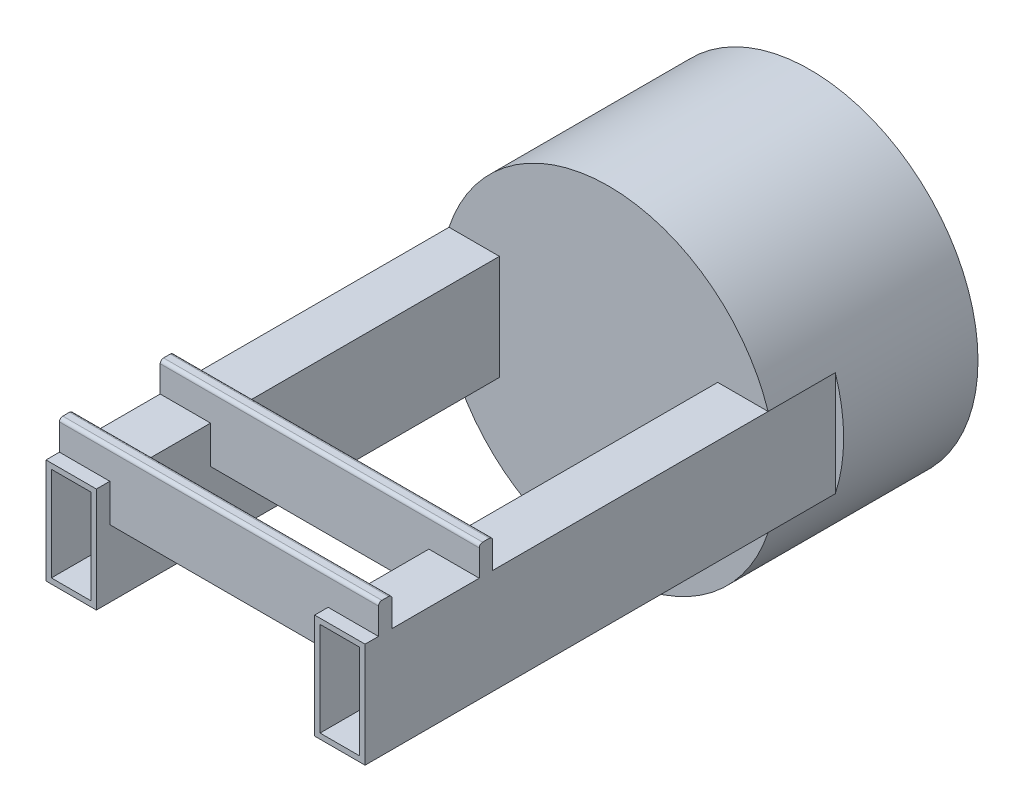
SolidWorks part; units mm, degrees
ref_plane "Ön Düzlem" through (0, 0, 0) normal (0, 0, 1) x (1, 0, 0)
ref_plane "Üst Düzlem" through (0, 0, 0) normal (0, 1, 0) x (1, 0, 0)
ref_plane "Sağ Düzlem" through (0, 0, 0) normal (1, 0, 0) x (0, 0, -1)
sketch "Çizim1" plane through (0, 0, 0) normal (0, 0, 1) x (1, 0, 0)
  line L0 (0, 265.92) -> (0, -189.5261) construction
  line L1 (-369.2295, 0) -> (436.5598, 0) construction
  line L2 (162.5, -78.0625) -> (162.5, 78.0625)
  line L3 (-162.5, -78.0625) -> (-237.5, -78.0625)
  line L4 (-162.5, -78.0625) -> (-162.5, 78.0625)
  line L5 (-162.5, 78.0625) -> (-237.5, 78.0625)
  line L6 (-237.5, -78.0625) -> (-237.5, 78.0625)
  line L7 (-162.5, -78.0625) -> (-237.5, 78.0625) construction
  line L8 (-162.5, 78.0625) -> (-237.5, -78.0625) construction
  line L9 (162.5, -78.0625) -> (237.5, -78.0625)
  line L10 (237.5, -78.0625) -> (237.5, 78.0625)
  line L11 (162.5, 78.0625) -> (237.5, 78.0625)
  arc A0 (-237.5, -78.0625) -> (237.5, -78.0625) centre (0, 0) ccw
  arc A1 (237.5, 78.0625) -> (-237.5, 78.0625) centre (0, 0) ccw
  point P7 (-200, 0)
  dimension "D1" = 500
  dimension "D2" = 200
  dimension "D3" = 75
extrude "Yükseklik-Ekstrüzyon2" add sketch "Çizim1" along normal blind 100 contours L11 A1 L5 L4 L3 A0 L9 L2 | L6 L3 L4 L5 | L11 L2 L9 L10
sketch "Çizim3" plane through (0, 0, 100) normal (0, 0, 1) x (1, 0, 0)
  line L0 (0, 0) -> (0, 358.8642) construction
  line L1 (0, 358.8642) -> (0, -328.59) construction
  line L2 (-380.3126, 0) -> (372.367, 0) construction
  line L3 (237.5, 78.0625) -> (237.5, -78.0625)
  line L4 (-237.5, 78.0625) -> (-162.5, 78.0625)
  line L5 (-237.5, 78.0625) -> (-237.5, -78.0625)
  line L6 (-237.5, -78.0625) -> (-162.5, -78.0625)
  line L7 (-162.5, 78.0625) -> (-162.5, -78.0625)
  line L8 (-237.5, 78.0625) -> (-162.5, -78.0625) construction
  line L9 (-237.5, -78.0625) -> (-162.5, 78.0625) construction
  line L10 (237.5, -78.0625) -> (162.5, -78.0625)
  line L11 (162.5, 78.0625) -> (162.5, -78.0625)
  line L12 (237.5, 78.0625) -> (162.5, 78.0625)
  point P6 (-200, 0)
  dimension "D1" = 200
  dimension "D2" = 75
extrude "Yükseklik-Ekstrüzyon3" add sketch "Çizim3" along normal blind 600
sketch "Çizim5" plane through (-237.5, 0, 0) normal (-1, 0, 0) x (0, 0, 1)
  line L0 (700, 78.0625) -> (700, -78.0625) construction
  line L1 (680, 22.0813) -> (660, 22.0813)
  line L2 (680, 22.0813) -> (680, 117.0813)
  line L3 (675, 122.0813) -> (665, 122.0813)
  line L4 (660, 22.0813) -> (660, 117.0813)
  line L5 (100, -78.0625) -> (700, -78.0625)
  line L6 (530, 22.0813) -> (510, 22.0813)
  line L7 (530, 22.0813) -> (530, 117.0813)
  line L8 (525, 122.0813) -> (515, 122.0813)
  line L9 (510, 22.0813) -> (510, 117.0813)
  arc A0 (680, 117.0813) -> (675, 122.0813) centre (675, 117.0813) ccw
  arc A1 (665, 122.0813) -> (660, 117.0813) centre (665, 117.0813) ccw
  arc A2 (530, 117.0813) -> (525, 122.0813) centre (525, 117.0813) ccw
  arc A3 (515, 122.0813) -> (510, 117.0813) centre (515, 117.0813) ccw
  point P9 (680, 122.0813)
  dimension "D4" = 5
  dimension "D6" = 5
  dimension "D1" = 20
  dimension "D2" = 20
  dimension "D3" = 100
  dimension "D5" = 20
  dimension "D7" = 130
extrude "Yükseklik-Ekstrüzyon9" add sketch "Çizim5" against normal through all contours L8 A3 L9 L4 L7 A2 | L9 L6 L7 L4 | L3 A1 L4 L2 A0 | L4 L1 L2
sketch "Çizim12" plane through (0, 0, 700) normal (0, 0, 1) x (1, 0, 0)
  line L0 (-162.5, 78.0625) -> (-237.5, 78.0625) construction
  line L1 (-170.5, -70.0625) -> (-229.5, -70.0625)
  line L2 (-170.5, -70.0625) -> (-170.5, 70.0625)
  line L3 (-170.5, 70.0625) -> (-229.5, 70.0625)
  line L4 (-229.5, -70.0625) -> (-229.5, 70.0625)
  line L5 (-170.5, -70.0625) -> (-229.5, 70.0625) construction
  line L6 (-170.5, 70.0625) -> (-229.5, -70.0625) construction
  line L7 (-237.5, 78.0625) -> (-237.5, -78.0625) construction
  line L8 (-237.5, -78.0625) -> (-162.5, -78.0625) construction
  line L9 (-162.5, -78.0625) -> (-162.5, 78.0625) construction
  line L10 (0, 148.0707) -> (0, -150.7872) construction
  line L11 (229.5, -70.0625) -> (229.5, 70.0625)
  line L12 (170.5, -70.0625) -> (229.5, -70.0625)
  line L13 (170.5, -70.0625) -> (170.5, 70.0625)
  line L14 (170.5, 70.0625) -> (229.5, 70.0625)
  point P0 (-200, 0)
  dimension "D1" = 8
  dimension "D2" = 8
  dimension "D3" = 8
  dimension "D4" = 8
extrude "Kes-Ekstrüzyon3" cut sketch "Çizim12" against normal through all
sketch "Çizim13" plane through (0, 0, 0) normal (0, 0, -1) x (-1, 0, 0)
  circle A0 centre (0, 0) radius 250
extrude "Yükseklik-Ekstrüzyon10" add sketch "Çizim13" along normal blind 200
sketch "Çizim15" plane through (0, 0, -200) normal (0, 0, -1) x (-1, 0, 0)
  circle A0 centre (0, 0) radius 225
  dimension "D1" = 450
extrude "Kes-Ekstrüzyon5" cut sketch "Çizim15" against normal blind 200
